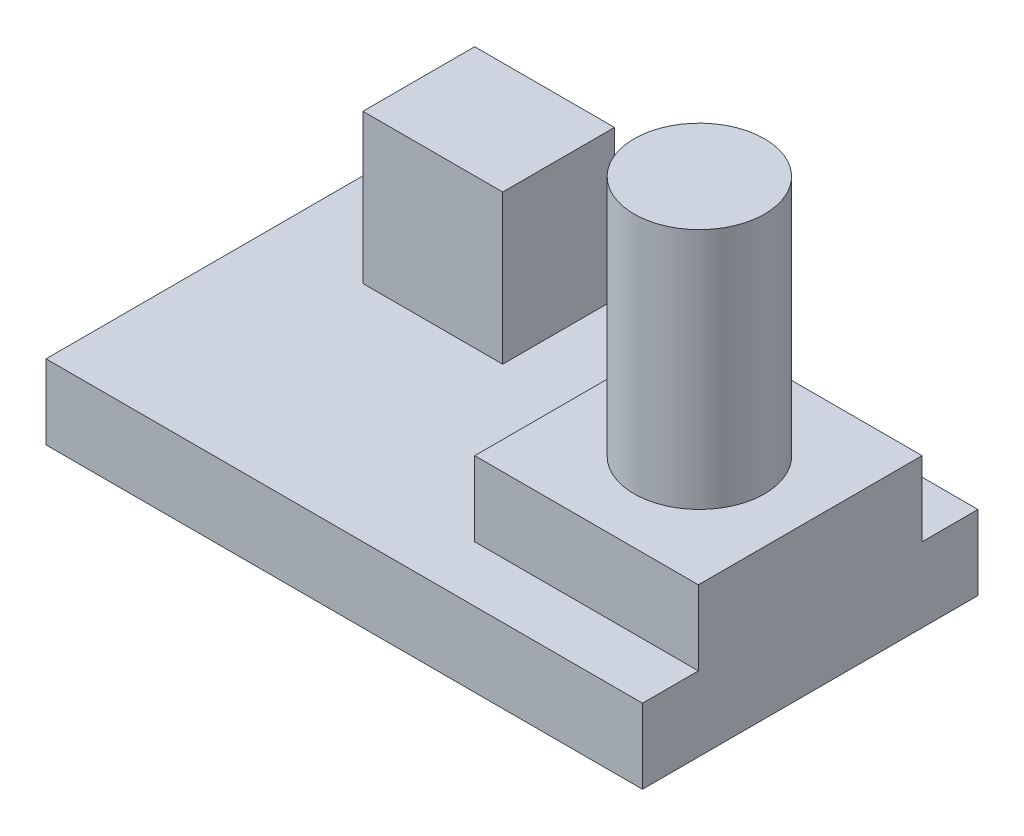
SolidWorks part; units mm, degrees
material "Epoxy, Unfilled"
ref_plane "Front Plane" through (0, 0, 0) normal (0, 0, 1) x (1, 0, 0)
ref_plane "Top Plane" through (0, 0, 0) normal (0, 1, 0) x (1, 0, 0)
ref_plane "Right Plane" through (0, 0, 0) normal (1, 0, 0) x (0, 0, -1)
sketch "Sketch1" plane through (0, 0, 0) normal (0, 1, 0) x (1, 0, 0)
  line L1 (-16, 9) -> (16, 9)
  line L2 (-16, 9) -> (-16, -9)
  line L3 (-16, -9) -> (16, -9)
  line L4 (16, 9) -> (16, -9)
  line L5 (-16, 9) -> (16, -9) construction
  line L6 (-16, -9) -> (16, 9) construction
  point P0 (0, 0)
  dimension "D1" = 32
  dimension "D2" = 18
extrude "PCB" add sketch "Sketch1" along normal blind 4
sketch "Sketch2" plane through (0, 4, 0) normal (0, 1, 0) x (1, 0, 0)
  line L0 (16, 9) -> (-16, 9) construction
  line L1 (-3.5, 3) -> (-11, 3)
  line L2 (-3.5, 3) -> (-3.5, 9)
  line L3 (-3.5, 9) -> (-11, 9)
  line L4 (-11, 3) -> (-11, 9)
  line L5 (-3.5, 3) -> (-11, 9) construction
  line L6 (-3.5, 9) -> (-11, 3) construction
  line L7 (-16, 9) -> (-16, -9) construction
  point P0 (-7.25, 6)
  dimension "D1" = 7.5
  dimension "D2" = 6
  dimension "D3" = 5
extrude "Connector" add sketch "Sketch2" along normal blind 8
sketch "Sketch3" plane through (0, 4, 0) normal (0, 1, 0) x (1, 0, 0)
  line L0 (16, -9) -> (16, 9) construction
  line L1 (4, 6) -> (16, 6)
  line L2 (4, 6) -> (4, -6)
  line L3 (4, -6) -> (16, -6)
  line L4 (16, 6) -> (16, -6)
  line L5 (4, 6) -> (16, -6) construction
  line L6 (4, -6) -> (16, 6) construction
  line L7 (16, -9) -> (16, 9) construction
  point P0 (10, 0)
  point P7 (0, 0)
  point P8 (16, 0)
  point P11 (16, 0)
  dimension "D1" = 12
  dimension "D2" = 12
extrude "Encoder" add sketch "Sketch3" along normal blind 4
sketch "Sketch4" plane through (0, 8, 0) normal (0, 1, 0) x (1, 0, 0)
  circle A0 centre (10.051, 0) radius 3.5
  dimension "D1" = 7
extrude "Boss-Extrude4" add sketch "Sketch4" along normal blind 13
